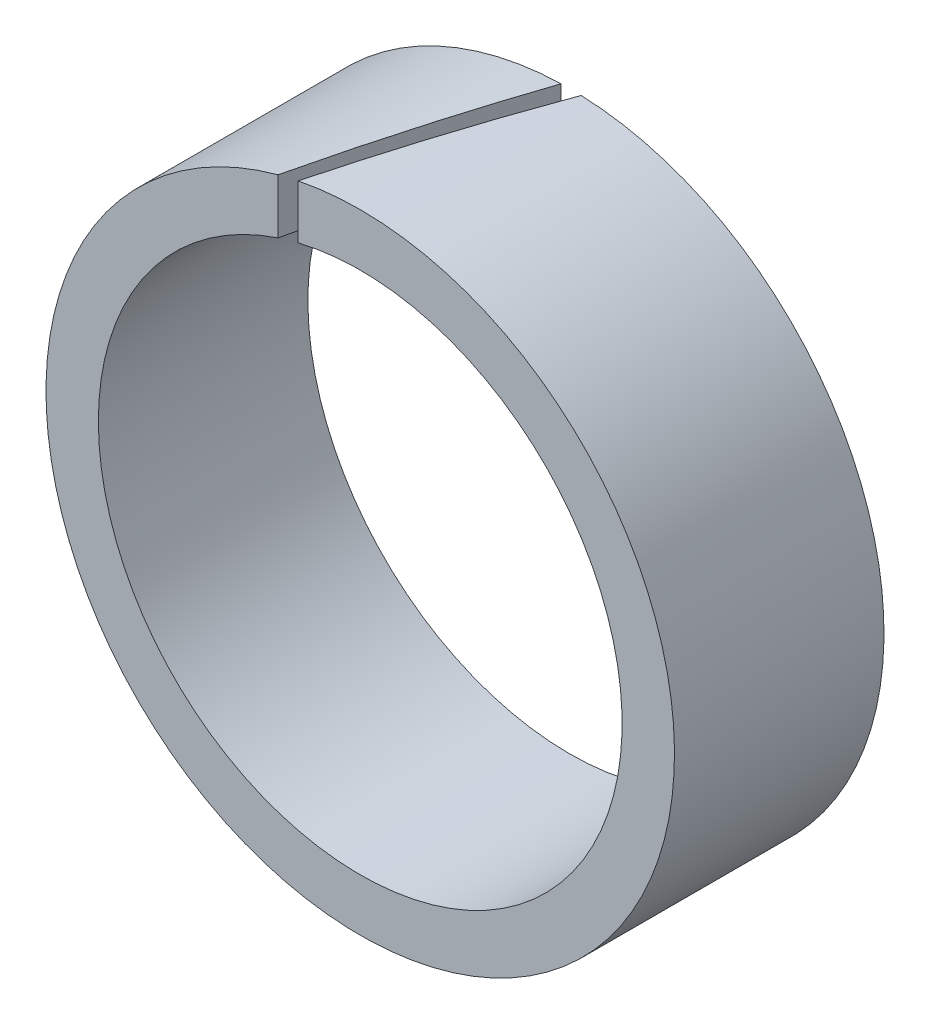
SolidWorks part; units mm, degrees
ref_plane "Front Plane" through (0, 0, 0) normal (0, 0, 1) x (1, 0, 0)
ref_plane "Top Plane" through (0, 0, 0) normal (0, 1, 0) x (1, 0, 0)
ref_plane "Right Plane" through (0, 0, 0) normal (1, 0, 0) x (0, 0, -1)
sketch "Sketch1" plane through (0, 0, 0) normal (0, 0, 1) x (1, 0, 0)
  circle A0 centre (0, 0) radius 12.5
  circle A1 centre (0, 0) radius 15
  dimension "D1" = 25
  dimension "D2" = 2.5
extrude "Boss-Extrude1" add sketch "Sketch1" along normal blind 10
ref_plane "Plane1" through (0, 15, 0) normal (0, 1, 0) x (1, 0, 0)
sketch "Sketch2" plane through (0, 15, 0) normal (0, 1, 0) x (1, 0, 0)
  line L0 (0.6931, 3.1544) -> (-4.707, -12.2282)
  line L1 (0.6931, 3.1544) -> (1.6069, 3.027)
  line L2 (-4.707, -12.2282) -> (-3.7932, -12.3556)
  line L3 (1.6069, 3.027) -> (-3.7932, -12.3556)
extrude "Cut-Extrude1" cut sketch "Sketch2" against normal blind 10
